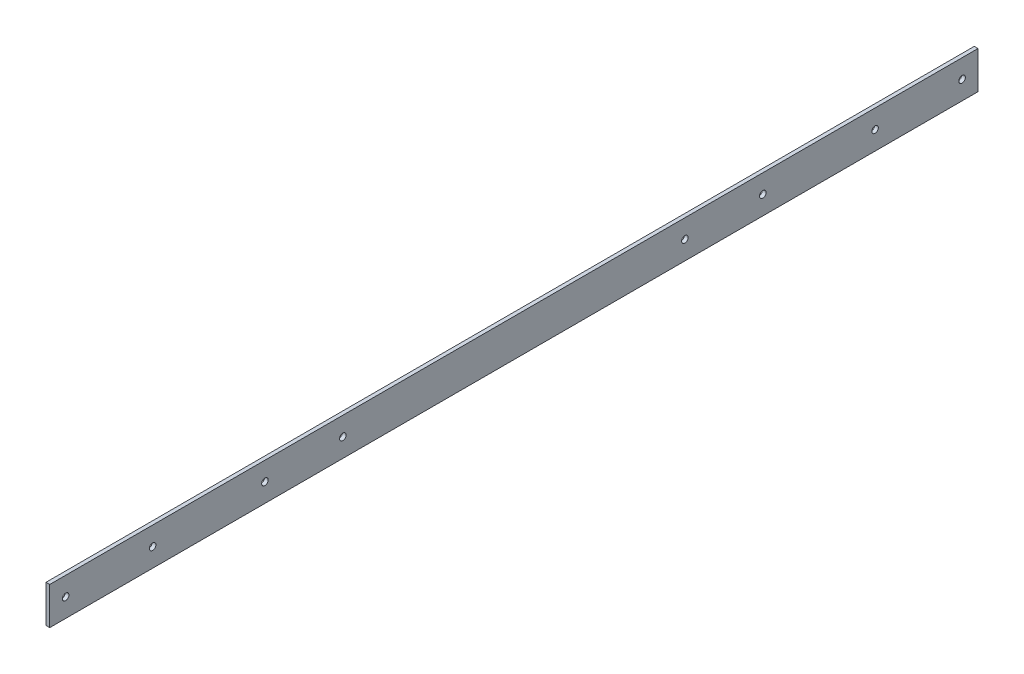
SolidWorks part; units mm, degrees
ref_plane "Спереди" through (0, 0, 0) normal (0, 0, 1) x (1, 0, 0)
ref_plane "Сверху" through (0, 0, 0) normal (0, 1, 0) x (1, 0, 0)
ref_plane "Справа" through (0, 0, 0) normal (1, 0, 0) x (0, 0, -1)
sketch "Эскиз1" plane through (0, 0, 0) normal (0, 0, 1) x (1, 0, 0)
  line L1 (0, 0) -> (2, 0)
  line L2 (0, 0) -> (0, 20)
  line L3 (0, 20) -> (2, 20)
  line L4 (2, 0) -> (2, 20)
  dimension "D1" = 20
  dimension "D2" = 2
extrude "Бобышка-Вытянуть1" add sketch "Эскиз1" along normal blind 496
sketch "Эскиз2" plane through (2, 0, 0) normal (1, 0, 0) x (0, 0, -1)
  line L0 (-496, 10) -> (0, 10) construction
  line L1 (-496, 0) -> (-496, 20) construction
  line L2 (0, 0) -> (0, 20) construction
  circle A0 centre (-487.5, 10) radius 1.75
  circle A1 centre (-441, 10) radius 1.75
  circle A2 centre (-381.01, 10) radius 1.75
  circle A3 centre (-339.4, 10) radius 1.75
  dimension "D1" = 3.5
  dimension "D2" = 8.5
  dimension "D3" = 55
  dimension "D5" = 101.6
  dimension "D4" = 41.61
extrude "Вырез-Вытянуть1" cut sketch "Эскиз2" against normal through all
ref_plane "Плоскость1" through (0, 0, 248) normal (0, 0, -1) x (-1, 0, 0)
mirror "Зеркальное отражение1" about plane through (0, 0, 248) normal (0, 0, -1) of "Вырез-Вытянуть1"
equation "\"ATX.Case.01.Dimension.1\"=499"
equation "\"ATX.Case.01.Profile.20.Thickness\" = 1.5"
equation "\"D1@Бобышка-Вытянуть1\"= \"ATX.Case.01.Dimension.1\" - \"ATX.Case.01.Profile.20.Thickness\" * 2"
equation "\"ATX.Case.01.Profile.20.Width\"=20"
equation "\"D2@Эскиз2\"= 0.5 * \"ATX.Case.01.Profile.20.Width\" - \"ATX.Case.01.Profile.20.Thickness\""
